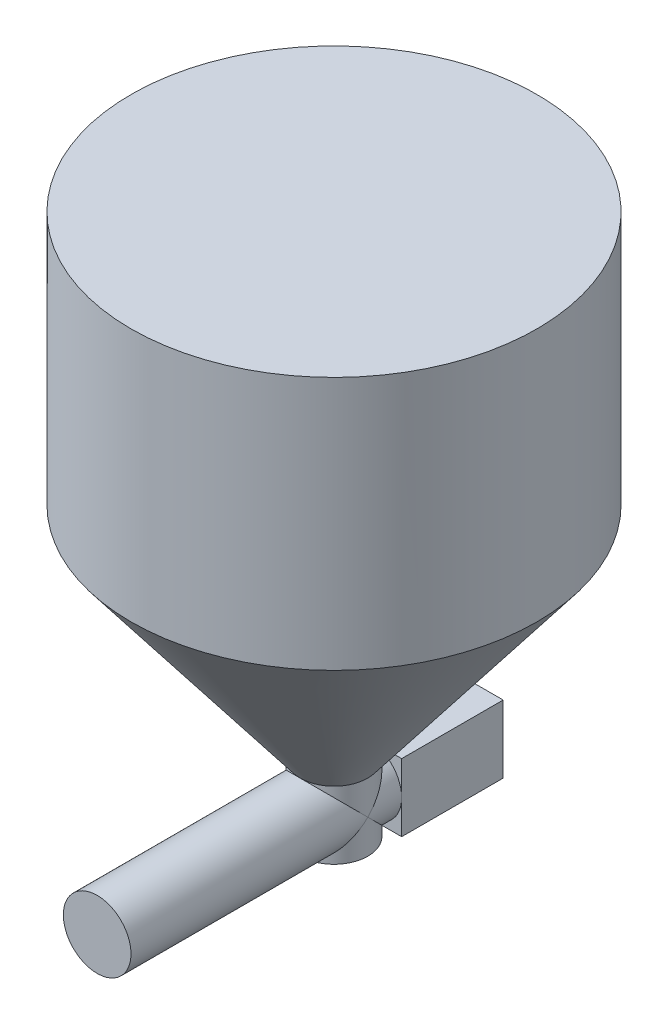
SolidWorks part; units mm, degrees
ref_plane "Alzado" through (0, 0, 0) normal (0, 0, 1) x (1, 0, 0)
ref_plane "Planta" through (0, 0, 0) normal (0, 1, 0) x (1, 0, 0)
ref_plane "Vista lateral" through (0, 0, 0) normal (1, 0, 0) x (0, 0, -1)
sketch "Croquis1" plane through (0, 0, 0) normal (0, 1, 0) x (1, 0, 0)
  circle A0 centre (0, 0) radius 300
  dimension "D1" = 600
ref_plane "Plano1" through (0, -700, 0) normal (0, 1, 0) x (1, 0, 0)
extrude "Saliente-Extruir1" add sketch "Croquis1" against normal blind 375 contours A0
sketch "Croquis2" plane through (0, -375, 0) normal (0, -1, 0) x (1, 0, 0)
  circle A0 centre (0, 0) radius 300
sketch "Croquis3" plane through (0, -700, 0) normal (0, 1, 0) x (1, 0, 0)
  circle A0 centre (0, 0) radius 50
  dimension "D1" = 100
loft "Recubrir1" add profiles "Croquis3", "Croquis2"
sketch "Croquis4" plane through (0, -700, 0) normal (0, -1, 0) x (1, 0, 0)
  circle A0 centre (0, 0) radius 50
extrude "Saliente-Extruir2" add sketch "Croquis4" along normal blind 100
ref_plane "Plano2" through (0, 0, -50) normal (0, 0, -1) x (-1, 0, 0)
sketch "Croquis5" plane through (0, 0, -50) normal (0, 0, -1) x (-1, 0, 0)
  line L0 (-50, -800) -> (50, -800) construction
  line L3 (0, -800) -> (0, -700) construction
  line L4 (330, -700) -> (-330, -700) construction
  circle A0 centre (0, -750) radius 50
extrude "Saliente-Extruir3" add sketch "Croquis5" against normal blind 400
sketch "Croquis6" plane through (0, 0, -50) normal (0, 0, -1) x (-1, 0, 0)
  line L0 (-50, -750) -> (50, -750) construction
  line L2 (-50, -700) -> (50, -700)
  line L3 (-50, -700) -> (-50, -800)
  line L4 (-50, -800) -> (50, -800)
  line L5 (50, -700) -> (50, -800)
  line L6 (-50, -700) -> (50, -800) construction
  line L7 (-50, -800) -> (50, -700) construction
  arc A0 (0, -700) -> (0, -800) centre (0, -750) ccw construction
  arc A1 (0, -800) -> (0, -700) centre (0, -750) ccw construction
  point P8 (0, -750)
  dimension "D1" = 100
  dimension "D2" = 100
extrude "Saliente-Extruir4" add sketch "Croquis6" along normal blind 150
